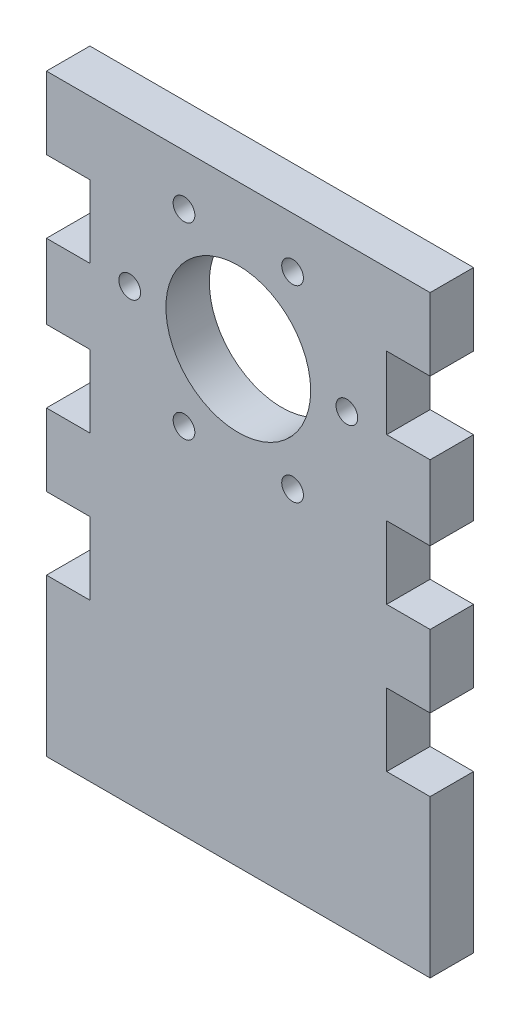
SolidWorks part; units mm, degrees
ref_plane "Alzado" through (0, 0, 0) normal (0, 0, 1) x (1, 0, 0)
ref_plane "Planta" through (0, 0, 0) normal (0, 1, 0) x (1, 0, 0)
ref_plane "Vista lateral" through (0, 0, 0) normal (1, 0, 0) x (0, 0, -1)
sketch "Sketch1" plane through (0, 0, 0) normal (0, 0, 1) x (1, 0, 0)
  line L0 (-13.25, 15.5) -> (-10.25, 15.5)
  line L1 (-13.25, 20.5) -> (13.25, 20.5)
  line L2 (-13.25, 20.5) -> (-13.25, 15.5)
  line L3 (-13.25, -20.5) -> (13.25, -20.5)
  line L4 (13.25, 20.5) -> (13.25, 15.5)
  line L5 (-13.25, 20.5) -> (13.25, -20.5) construction
  line L6 (-13.25, -20.5) -> (13.25, 20.5) construction
  line L7 (-10.25, 15.5) -> (-10.25, 10.5)
  line L8 (-10.25, 10.5) -> (-13.25, 10.5)
  line L9 (-13.25, 5.35) -> (-10.25, 5.35)
  line L10 (-10.25, 5.35) -> (-10.25, 0.35)
  line L11 (-10.25, 0.35) -> (-13.25, 0.35)
  line L12 (-13.25, -4.65) -> (-10.25, -4.65)
  line L13 (-10.25, -4.65) -> (-10.25, -9.65)
  line L14 (-10.25, -9.65) -> (-13.25, -9.65)
  line L15 (0, 20.5) -> (0, -20.5) construction
  line L16 (10.25, -9.65) -> (13.25, -9.65)
  line L17 (10.25, -4.65) -> (10.25, -9.65)
  line L18 (13.25, -4.65) -> (10.25, -4.65)
  line L19 (10.25, 0.35) -> (13.25, 0.35)
  line L20 (10.25, 5.35) -> (10.25, 0.35)
  line L21 (13.25, 5.35) -> (10.25, 5.35)
  line L22 (10.25, 10.5) -> (13.25, 10.5)
  line L23 (10.25, 15.5) -> (10.25, 10.5)
  line L24 (13.25, 15.5) -> (10.25, 15.5)
  line L25 (-13.25, 10.5) -> (-13.25, 5.35)
  line L26 (-13.25, 0.35) -> (-13.25, -4.65)
  line L27 (-13.25, -9.65) -> (-13.25, -20.5)
  line L28 (13.25, -9.65) -> (13.25, -20.5)
  line L29 (13.25, 0.35) -> (13.25, -4.65)
  line L30 (13.25, 10.5) -> (13.25, 5.35)
  line L31 (-3.75, 16.9952) -> (3.75, 4.0048) construction
  line L32 (7.5, 10.4998) -> (-7.5, 10.5002) construction
  line L33 (3.75, 16.9952) -> (-3.75, 4.0048) construction
  circle A0 centre (0, 10.5) radius 5
  circle A1 centre (0, 10.5) radius 7.5 construction
  circle A2 centre (3.75, 16.9952) radius 0.75
  circle A3 centre (7.5, 10.4998) radius 0.75
  circle A4 centre (3.75, 4.0048) radius 0.75
  circle A5 centre (-3.75, 4.0048) radius 0.75
  circle A6 centre (-7.5, 10.5002) radius 0.75
  circle A7 centre (-3.75, 16.9952) radius 0.75
  point P0 (0, 0)
  point P49 (0, 10.5)
  point P50 (0, 10.5)
  dimension "D8" = 10
  dimension "D10" = 15
  dimension "D11" = 1.5
  dimension "D1" = 26.5
  dimension "D2" = 41
  dimension "D3" = 3
  dimension "D4" = 5
  dimension "D5" = 5
  dimension "D6" = 5.15
  dimension "D7" = 5
  dimension "D9" = 10
  dimension "D12" = 30
  dimension "D13" = 59.998
  dimension "D14" = 30
extrude "Boss-Extrude1" add sketch "Sketch1" along normal blind 3
